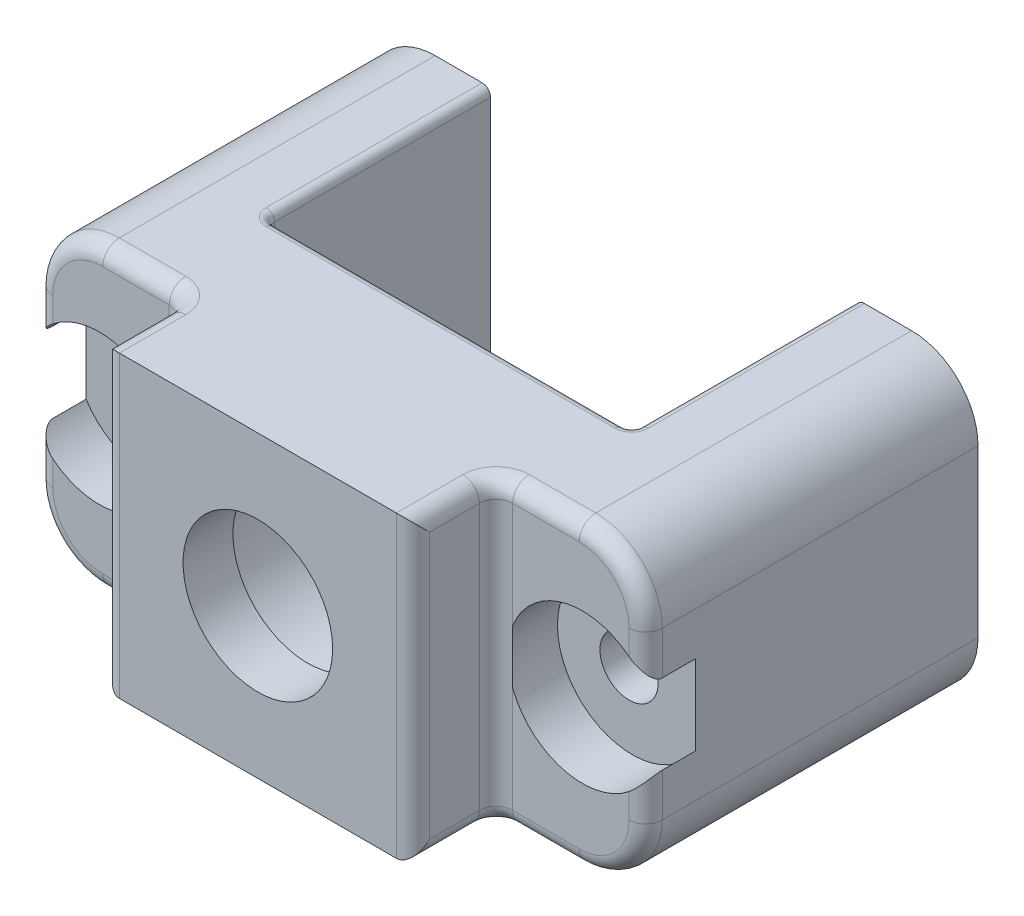
SolidWorks part; units mm, degrees
ref_plane "Front Plane" through (0, 0, 0) normal (0, 0, 1) x (1, 0, 0)
ref_plane "Top Plane" through (0, 0, 0) normal (0, 1, 0) x (1, 0, 0)
ref_plane "Right Plane" through (0, 0, 0) normal (1, 0, 0) x (0, 0, -1)
sketch "Sketch1" plane through (0, 0, 0) normal (0, 0, 1) x (1, 0, 0)
  line L0 (0, 9) -> (0, 13.2219) construction
  line L1 (-14.3348, 9) -> (14.3348, 9)
  line L2 (-18.3348, 5) -> (-18.3348, -5)
  line L3 (-14.3348, -9) -> (14.3348, -9)
  line L4 (18.3348, 5) -> (18.3348, -5)
  line L5 (-18.3348, 9) -> (18.3348, -9) construction
  line L6 (-18.3348, -9) -> (18.3348, 9) construction
  circle A0 centre (0, 0) radius 5.5
  circle A2 centre (-14.3348, 0) radius 1.75
  arc A3 (14.3348, 9) -> (18.3348, 5) centre (14.3348, 5) cw
  arc A4 (14.3348, -9) -> (18.3348, -5) centre (14.3348, -5) ccw
  arc A5 (-18.3348, -5) -> (-14.3348, -9) centre (-14.3348, -5) ccw
  arc A6 (-14.3348, 9) -> (-18.3348, 5) centre (-14.3348, 5) ccw
  circle A7 centre (14.3348, 0) radius 1.75
  dimension "D1" = 11
  dimension "D2" = 9
  dimension "D3" = 3.5
  dimension "D4" = 4
  dimension "D5" = 4
extrude "Boss-Extrude1" add sketch "Sketch1" along normal blind 15
sketch "Sketch3" plane through (0, 0, 15) normal (0, 0, 1) x (1, 0, 0)
  line L1 (-9.3348, 10.683) -> (-19.3342, 10.683)
  line L2 (-9.3348, 10.683) -> (-9.3348, -11.5423)
  line L3 (-9.3348, -11.5423) -> (-19.3342, -11.5423)
  line L4 (-19.3342, 10.683) -> (-19.3342, -11.5423)
  circle A1 centre (-14.3348, 0) radius 1.75 construction
  dimension "D1" = 5
extrude "Cut-Extrude1" cut sketch "Sketch3" against normal blind 5
fillet "Fillet1" radius 1 9 edges at (-11.8348, 9, 10) (-9.3348, 0, 10) (-11.8348, -9, 10) (-17.1632, -7.8284, 10) (-18.3348, 0, 10) (-17.1632, 7.8284, 10) (-9.3348, 9, 12.5) (-9.3348, -9, 12.5) (-9.3348, 0, 15)
mirror "Mirror1" about plane through (0, 0, 0) normal (1, 0, 0) of "Cut-Extrude1", "Fillet1"
sketch "Sketch4" plane through (0, 0, 15) normal (0, 0, 1) x (1, 0, 0)
  circle A0 centre (0, 0) radius 7.5
  dimension "D1" = 15
extrude "Boss-Extrude2" add sketch "Sketch4" against normal blind 3
sketch "Sketch5" plane through (0, 9, 0) normal (0, 1, 0) x (1, 0, 0)
  line L1 (-11, 3.5) -> (11, 3.5)
  line L2 (-11, 3.5) -> (-11, -3.5)
  line L3 (-11, -3.5) -> (11, -3.5)
  line L4 (11, 3.5) -> (11, -3.5)
  line L5 (-11, 3.5) -> (11, -3.5) construction
  line L6 (-11, -3.5) -> (11, 3.5) construction
  line L7 (14.3348, 0) -> (-14.3348, 0) construction
  point P0 (0, 0)
  dimension "D1" = 22
  dimension "D2" = 3.5
extrude "Cut-Extrude2" cut sketch "Sketch5" against normal through all
sketch "Sketch6" plane through (0, 0, 15) normal (0, 0, 1) x (1, 0, 0)
  circle A0 centre (0, 0) radius 4.5
  dimension "D1" = 9
extrude "Cut-Extrude3" cut sketch "Sketch6" against normal through all
sketch "Sketch7" plane through (0, 0, 10) normal (0, 0, 1) x (1, 0, 0)
  circle A0 centre (-14.5304, 0) radius 4.5
  circle A1 centre (14.5304, 0) radius 4.5
  dimension "D1" = 9
  dimension "D2" = 9
extrude "Cut-Extrude8" cut sketch "Sketch7" against normal blind 3
fillet "Fillet3" radius 0.5 8 edges at (-11, 0, 3.5) (0, -9, 3.5) (11, 0, 3.5) (0, 9, 3.5) (-11, -9, 1.75) (11, -9, 1.75) (11, 9, 1.75) (-11, 9, 1.75)
fillet "Fillet2" radius 0.5 1 edges at (5.5, 0, 12)
sketch "Sketch8" plane through (0, 0, 0) normal (0, 0, -1) x (-1, 0, 0)
  line L4 (11, 8.5) -> (11, -8.5)
  line L5 (11.5, -9) -> (14.3348, -9)
  line L6 (18.3348, -5) -> (18.3348, 5)
  line L7 (14.3348, 9) -> (11.5, 9)
  line L8 (11, 8.5) -> (11, -8.5)
  line L9 (11.5, -9) -> (14.3348, -9)
  line L10 (18.3348, -5) -> (18.3348, 5)
  line L11 (14.3348, 9) -> (11.5, 9)
  line L12 (-14.3348, -9) -> (-11.5, -9)
  line L13 (-11, -8.5) -> (-11, 8.5)
  line L14 (-11.5, 9) -> (-14.3348, 9)
  line L15 (-18.3348, 5) -> (-18.3348, -5)
  line L16 (-14.3348, -9) -> (-11.5, -9)
  line L17 (-11, -8.5) -> (-11, 8.5)
  line L18 (-11.5, 9) -> (-14.3348, 9)
  line L19 (-18.3348, 5) -> (-18.3348, -5)
  circle A0 centre (14.3348, 0) radius 1.75 construction
  circle A1 centre (-14.3348, 0) radius 1.75
  circle A2 centre (-14.3348, 0) radius 1.75
  circle A3 centre (14.3348, 0) radius 1.75
  arc A4 (11, -8.5) -> (11.5, -9) centre (11.5, -8.5) ccw
  arc A5 (14.3348, -9) -> (18.3348, -5) centre (14.3348, -5) ccw
  arc A6 (18.3348, 5) -> (14.3348, 9) centre (14.3348, 5) ccw
  arc A7 (11.5, 9) -> (11, 8.5) centre (11.5, 8.5) ccw
  arc A8 (11, -8.5) -> (11.5, -9) centre (11.5, -8.5) ccw
  arc A9 (14.3348, -9) -> (18.3348, -5) centre (14.3348, -5) ccw
  arc A10 (18.3348, 5) -> (14.3348, 9) centre (14.3348, 5) ccw
  arc A11 (11.5, 9) -> (11, 8.5) centre (11.5, 8.5) ccw
  arc A16 (-11.5, -9) -> (-11, -8.5) centre (-11.5, -8.5) ccw
  arc A17 (-11, 8.5) -> (-11.5, 9) centre (-11.5, 8.5) ccw
  arc A18 (-14.3348, 9) -> (-18.3348, 5) centre (-14.3348, 5) ccw
  arc A19 (-18.3348, -5) -> (-14.3348, -9) centre (-14.3348, -5) ccw
  arc A20 (-11.5, -9) -> (-11, -8.5) centre (-11.5, -8.5) ccw
  arc A21 (-11, 8.5) -> (-11.5, 9) centre (-11.5, 8.5) ccw
  arc A22 (-14.3348, 9) -> (-18.3348, 5) centre (-14.3348, 5) ccw
  arc A23 (-18.3348, -5) -> (-14.3348, -9) centre (-14.3348, -5) ccw
  dimension "D1" = 0
  dimension "D2" = 0
  dimension "D3" = 0
extrude "Boss-Extrude3" add sketch "Sketch8" along normal blind 10
